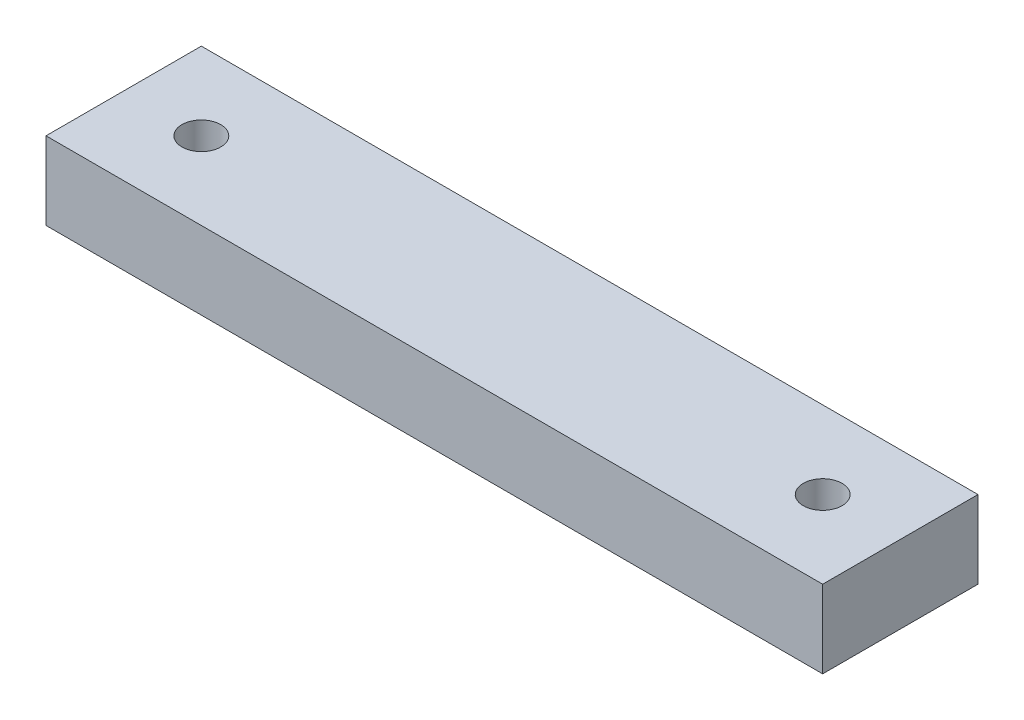
SolidWorks part; units mm, degrees
ref_plane "前视基准面" through (0, 0, 0) normal (0, 0, 1) x (1, 0, 0)
ref_plane "上视基准面" through (0, 0, 0) normal (0, 1, 0) x (1, 0, 0)
ref_plane "右视基准面" through (0, 0, 0) normal (1, 0, 0) x (0, 0, -1)
sketch "草图1" plane through (0, 0, 0) normal (0, 1, 0) x (1, 0, 0)
  line L0 (-59.4148, 0) -> (82.57, 0) construction
  line L1 (-50, -10) -> (50, -10)
  line L2 (-50, -10) -> (-50, 10)
  line L3 (-50, 10) -> (50, 10)
  line L4 (50, -10) -> (50, 10)
  line L5 (-50, -10) -> (50, 10) construction
  line L6 (-50, 10) -> (50, -10) construction
  circle A0 centre (-40, 0) radius 2.5
  circle A1 centre (40, 0) radius 2.5
  point P0 (0, 0)
  dimension "D3" = 5
  dimension "D4" = 5
  dimension "D5" = 40
  dimension "D6" = 40
  dimension "D1" = 100
  dimension "D2" = 20
extrude "凸台-拉伸1" add sketch "草图1" along normal blind 10
ref_point "点1"
